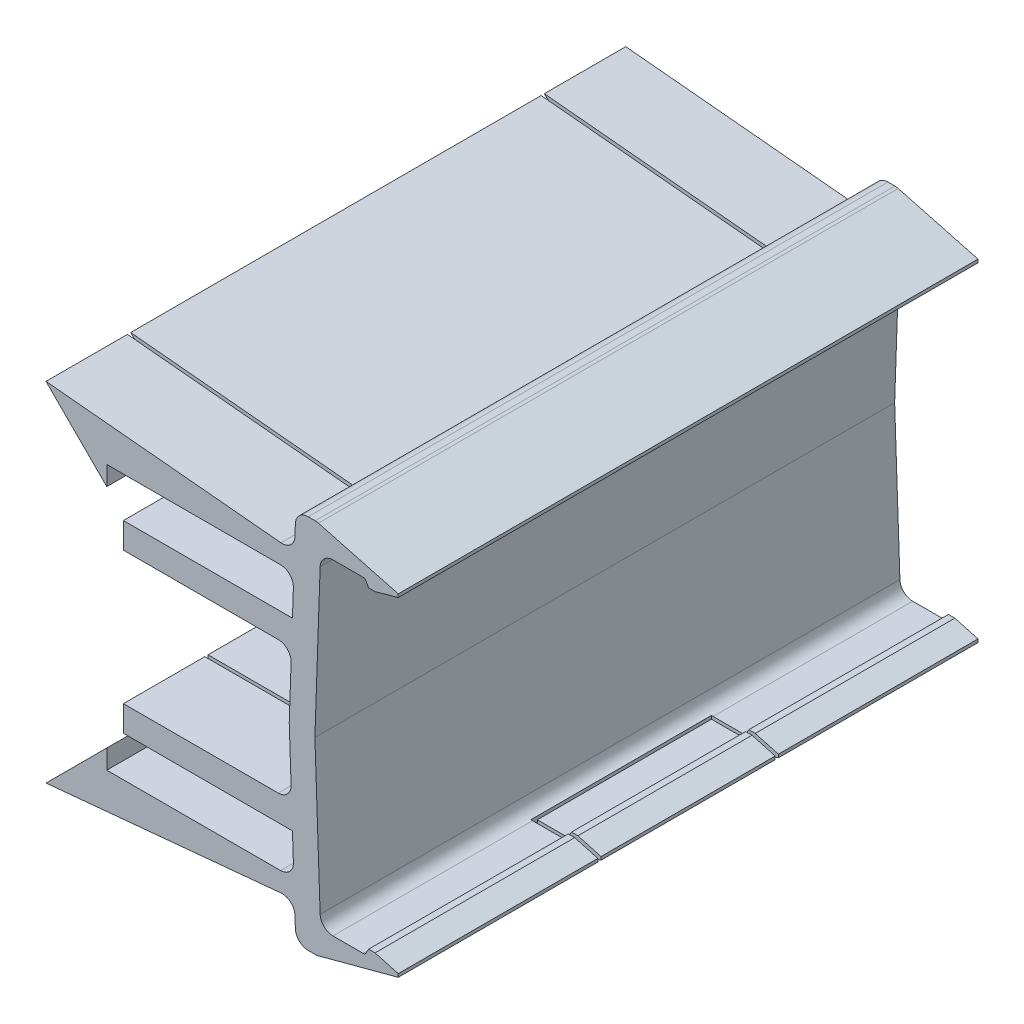
SolidWorks part; units mm, degrees
ref_plane "Front Plane" through (0, 0, 0) normal (0, 0, 1) x (1, 0, 0)
ref_plane "Top Plane" through (0, 0, 0) normal (0, 1, 0) x (1, 0, 0)
ref_plane "Right Plane" through (0, 0, 0) normal (1, 0, 0) x (0, 0, -1)
sketch "Sketch1" plane through (0, 0, 0) normal (0, 0, 1) x (1, 0, 0)
  line L50 (-6.5001, 0) -> (-6.0903, 11.7349) construction
  line L51 (-3.9751, 12.7) -> (-5.0909, 12.7) construction
  line L52 (-3.9751, 12.7) -> (-2.7386, 12.7) construction
  line L53 (-2.5221, 12.575) -> (-2.3056, 12.2) construction
  line L54 (-2.3056, 12.2) -> (-1.8056, 12.2) construction
  line L55 (-1.8056, 12.2) -> (0, 12.7) construction
  line L56 (0, 12.7) -> (0, 12.95) construction
  line L57 (0, 12.95) -> (-6.35, 14.6455) construction
  line L58 (-6.35, 14.6455) -> (-7.9899, 14.6455) construction
  line L59 (-8.5013, 0) -> (-7.9899, 14.6455) construction
  line L60 (-8.5013, 0) -> (-7.9899, -14.6455) construction
  line L61 (-6.35, -14.6455) -> (-7.9899, -14.6455) construction
  line L62 (0, -12.95) -> (-6.35, -14.6455) construction
  line L63 (0, -12.7) -> (0, -12.95) construction
  line L64 (-1.8056, -12.2) -> (0, -12.7) construction
  line L65 (-2.3056, -12.2) -> (-1.8056, -12.2) construction
  line L66 (-2.5221, -12.575) -> (-2.3056, -12.2) construction
  line L67 (-3.9751, -12.7) -> (-2.7386, -12.7) construction
  line L68 (-3.9751, -12.7) -> (-5.0909, -12.7) construction
  line L69 (-6.5001, 0) -> (-6.0903, -11.7349) construction
  line L70 (-6.5001, 0) -> (-6.0903, 11.7349)
  line L71 (-3.9751, 12.7) -> (-5.0909, 12.7)
  line L72 (-3.9751, 12.7) -> (-2.7386, 12.7)
  line L73 (-2.5221, 12.575) -> (-2.3056, 12.2)
  line L74 (-2.3056, 12.2) -> (-1.8056, 12.2)
  line L75 (-1.8056, 12.2) -> (0, 12.7)
  line L76 (0, 12.7) -> (0, 12.95)
  line L77 (0, 12.95) -> (-6.35, 14.6455)
  line L78 (-6.35, 14.6455) -> (-7.9899, 14.6455)
  line L79 (-8.5013, 0) -> (-7.9899, 14.6455)
  line L80 (-8.5013, 0) -> (-7.9899, -14.6455)
  line L81 (-6.35, -14.6455) -> (-7.9899, -14.6455)
  line L82 (0, -12.95) -> (-6.35, -14.6455)
  line L83 (0, -12.7) -> (0, -12.95)
  line L84 (-1.8056, -12.2) -> (0, -12.7)
  line L85 (-2.3056, -12.2) -> (-1.8056, -12.2)
  line L86 (-2.5221, -12.575) -> (-2.3056, -12.2)
  line L87 (-3.9751, -12.7) -> (-2.7386, -12.7)
  line L88 (-3.9751, -12.7) -> (-5.0909, -12.7)
  line L89 (-6.5001, 0) -> (-6.0903, -11.7349)
  arc A10 (-5.0909, 12.7) -> (-6.0903, 11.7349) centre (-5.0909, 11.7) ccw construction
  arc A11 (-2.5221, 12.575) -> (-2.7386, 12.7) centre (-2.7386, 12.45) ccw construction
  arc A12 (-2.7386, -12.7) -> (-2.5221, -12.575) centre (-2.7386, -12.45) ccw construction
  arc A13 (-6.0903, -11.7349) -> (-5.0909, -12.7) centre (-5.0909, -11.7) ccw construction
  arc A14 (-5.0909, 12.7) -> (-6.0903, 11.7349) centre (-5.0909, 11.7) ccw
  arc A15 (-2.5221, 12.575) -> (-2.7386, 12.7) centre (-2.7386, 12.45) ccw
  arc A16 (-2.7386, -12.7) -> (-2.5221, -12.575) centre (-2.7386, -12.45) ccw
  arc A17 (-6.0903, -11.7349) -> (-5.0909, -12.7) centre (-5.0909, -11.7) ccw
extrude "Boss-Extrude1" add sketch "Sketch1" along normal mid plane 6.35
sketch "Sketch3" plane through (0, 0, 0) normal (0, 0, 1) x (1, 0, 0)
  line L1 (-21.435, 5.1835) -> (-8.2505, 5.1835)
  line L2 (-21.435, 5.1835) -> (-21.435, 7.1835)
  line L3 (-21.435, 7.1835) -> (-8.2505, 7.1835)
  line L4 (-8.2505, 5.1835) -> (-8.2505, 7.1835)
  line L5 (-21.435, -10.3251) -> (-21.435, 10.3251) construction
  line L6 (-13.335, 7.6835) -> (-15.875, 7.6835) construction
  line L7 (-7.9899, 14.6455) -> (-8.5013, 0) construction
  dimension "D1" = 2
  dimension "D2" = 0.5
sketch "Sketch2" plane through (0, 0, 0) normal (0, 0, 1) x (1, 0, 0)
  line L0 (-22.7304, 10.3251) -> (-22.7304, 8.8251)
  line L1 (-22.7304, 8.8251) -> (-27.4693, 13.564)
  line L2 (-27.4693, 13.564) -> (-8.0919, 11.7251)
  line L3 (-8.0919, 11.7251) -> (-8.0919, 10.3251)
  line L4 (-8.0919, 10.3251) -> (-22.7304, 10.3251)
  line L5 (-22.7304, 10.3251) -> (-22.7304, 11.3751) construction
  line L6 (-15.875, 10.3251) -> (-17.018, 10.3251) construction
  line L9 (-7.9899, 14.6455) -> (-8.5013, 0) construction
  line L10 (-22.578, -10.3251) -> (-22.578, 10.3251) construction
  dimension "D1" = 1.05
  dimension "D2" = 1.4
  dimension "D4" = 1.5
  dimension "D5" = 45
  dimension "D3" = 0.1524
extrude "Boss-Extrude2" add sketch "Sketch2" along normal up to surface and the other way up to surface
extrude "Boss-Extrude3" add sketch "Sketch3" along normal up to surface and the other way up to surface
fillet "Fillet1" radius 1 5 edges at (-8.3203, 5.1835, 0) (-8.1408, 10.3251, 0) (-8.0919, 11.7251, 0) (-6.35, 14.6455, 0) (-7.9899, 14.6455, 0)
sketch "Sketch9" plane through (0, 0, 0) normal (0, 0, 1) x (1, 0, 0)
  line L7 (-7.9899, -14.6455) -> (-6.35, -14.6455) construction
  line L8 (0, 0) -> (-14.6455, 0)
  line L9 (0, 0) -> (0, -14.6455)
  line L10 (0, -14.6455) -> (-14.6455, -14.6455)
  line L11 (-14.6455, 0) -> (-14.6455, -14.6455)
extrude "Cut-Extrude4" cut sketch "Sketch9" against normal through all both and the other way through all
mirror "Mirror2" about plane through (0, 0, 0) normal (0, 1, 0) of bodies 110 103
ref_plane "Plane1" through (0, 0, 0) normal (0, 0, 1) x (1, 0, 0)
ref_plane "Plane2" through (0, 0, 0) normal (0, 1, 0) x (1, 0, 0)
ref_plane "Plane3" through (0, 0, 0) normal (0, 0, 1) x (1, 0, 0)
ref_plane "Plane4" through (0, 0, 19.431) normal (0, 0, 1) x (1, 0, 0)
ref_plane "Plane5" through (0, 0, 42.037) normal (0, 0, 1) x (1, 0, 0)
sketch "Sketch10" plane through (0, 0, 42.037) normal (0, 0, 1) x (1, 0, 0)
  line L36 (-8.3564, 4.1486) -> (-8.5013, 0)
  line L37 (-8.5013, 0) -> (-8.3564, -4.1486)
  line L38 (-9.3558, -5.1835) -> (-21.435, -5.1835)
  line L39 (-21.435, -5.1835) -> (-21.435, -7.1835)
  line L40 (-21.435, -7.1835) -> (-8.2505, -7.1835)
  line L41 (-8.2505, -7.1835) -> (-8.1769, -9.2902)
  line L42 (-9.1763, -10.3251) -> (-22.7304, -10.3251)
  line L43 (-22.7304, -10.3251) -> (-22.7304, -8.8251)
  line L44 (-22.7304, -8.8251) -> (-27.4693, -13.564)
  line L45 (-27.4693, -13.564) -> (-9.1487, -11.8254)
  line L46 (-8.0548, -12.786) -> (-8.0236, -13.6804)
  line L47 (-7.0242, -14.6455) -> (-6.4812, -14.6455)
  line L48 (-6.2232, -14.6117) -> (0, -12.95)
  line L49 (0, -12.95) -> (0, -12.7)
  line L50 (0, -12.7) -> (-1.8056, -12.2)
  line L51 (-1.8056, -12.2) -> (-2.3056, -12.2)
  line L52 (-2.3056, -12.2) -> (-2.5221, -12.575)
  line L53 (-2.7386, -12.7) -> (-5.0909, -12.7)
  line L54 (-6.0903, -11.7349) -> (-6.5001, 0)
  line L55 (-6.5001, 0) -> (-6.0903, 11.7349)
  line L56 (-5.0909, 12.7) -> (-2.7386, 12.7)
  line L57 (-2.5221, 12.575) -> (-2.3056, 12.2)
  line L58 (-2.3056, 12.2) -> (-1.8056, 12.2)
  line L59 (-1.8056, 12.2) -> (0, 12.7)
  line L60 (0, 12.7) -> (0, 12.95)
  line L61 (0, 12.95) -> (-6.2232, 14.6117)
  line L62 (-6.4812, 14.6455) -> (-7.0242, 14.6455)
  line L63 (-8.0236, 13.6804) -> (-8.0548, 12.786)
  line L64 (-9.1487, 11.8254) -> (-27.4693, 13.564)
  line L65 (-27.4693, 13.564) -> (-22.7304, 8.8251)
  line L66 (-22.7304, 8.8251) -> (-22.7304, 10.3251)
  line L67 (-22.7304, 10.3251) -> (-9.1763, 10.3251)
  line L68 (-8.1769, 9.2902) -> (-8.2505, 7.1835)
  line L69 (-8.2505, 7.1835) -> (-21.435, 7.1835)
  line L70 (-21.435, 7.1835) -> (-21.435, 5.1835)
  line L71 (-21.435, 5.1835) -> (-9.3558, 5.1835)
  line L72 (-8.3564, 4.1486) -> (-8.5013, 0)
  line L73 (-8.5013, 0) -> (-8.3564, -4.1486)
  line L74 (-9.3558, -5.1835) -> (-21.435, -5.1835)
  line L75 (-21.435, -5.1835) -> (-21.435, -7.1835)
  line L76 (-21.435, -7.1835) -> (-8.2505, -7.1835)
  line L77 (-8.2505, -7.1835) -> (-8.1769, -9.2902)
  line L78 (-9.1763, -10.3251) -> (-22.7304, -10.3251)
  line L79 (-22.7304, -10.3251) -> (-22.7304, -8.8251)
  line L80 (-22.7304, -8.8251) -> (-27.4693, -13.564)
  line L81 (-27.4693, -13.564) -> (-9.1487, -11.8254)
  line L82 (-8.0548, -12.786) -> (-8.0236, -13.6804)
  line L83 (-7.0242, -14.6455) -> (-6.4812, -14.6455)
  line L84 (-6.2232, -14.6117) -> (0, -12.95)
  line L85 (0, -12.95) -> (0, -12.7)
  line L86 (0, -12.7) -> (-1.8056, -12.2)
  line L87 (-1.8056, -12.2) -> (-2.3056, -12.2)
  line L88 (-2.3056, -12.2) -> (-2.5221, -12.575)
  line L89 (-2.7386, -12.7) -> (-5.0909, -12.7)
  line L90 (-6.0903, -11.7349) -> (-6.5001, 0)
  line L91 (-6.5001, 0) -> (-6.0903, 11.7349)
  line L92 (-5.0909, 12.7) -> (-2.7386, 12.7)
  line L93 (-2.5221, 12.575) -> (-2.3056, 12.2)
  line L94 (-2.3056, 12.2) -> (-1.8056, 12.2)
  line L95 (-1.8056, 12.2) -> (0, 12.7)
  line L96 (0, 12.7) -> (0, 12.95)
  line L97 (0, 12.95) -> (-6.2232, 14.6117)
  line L98 (-6.4812, 14.6455) -> (-7.0242, 14.6455)
  line L99 (-8.0236, 13.6804) -> (-8.0548, 12.786)
  line L100 (-9.1487, 11.8254) -> (-27.4693, 13.564)
  line L101 (-27.4693, 13.564) -> (-22.7304, 8.8251)
  line L102 (-22.7304, 8.8251) -> (-22.7304, 10.3251)
  line L103 (-22.7304, 10.3251) -> (-9.1763, 10.3251)
  line L104 (-8.1769, 9.2902) -> (-8.2505, 7.1835)
  line L105 (-8.2505, 7.1835) -> (-21.435, 7.1835)
  line L106 (-21.435, 7.1835) -> (-21.435, 5.1835)
  line L107 (-21.435, 5.1835) -> (-9.3558, 5.1835)
  arc A14 (-9.3558, -5.1835) -> (-8.3564, -4.1486) centre (-9.3558, -4.1835) ccw
  arc A15 (-9.1763, -10.3251) -> (-8.1769, -9.2902) centre (-9.1763, -9.3251) ccw
  arc A16 (-8.0548, -12.786) -> (-9.1487, -11.8254) centre (-9.0542, -12.8209) ccw
  arc A17 (-8.0236, -13.6804) -> (-7.0242, -14.6455) centre (-7.0242, -13.6455) ccw
  arc A18 (-6.4812, -14.6455) -> (-6.2232, -14.6117) centre (-6.4812, -13.6455) ccw
  arc A19 (-2.7386, -12.7) -> (-2.5221, -12.575) centre (-2.7386, -12.45) ccw
  arc A20 (-6.0903, -11.7349) -> (-5.0909, -12.7) centre (-5.0909, -11.7) ccw
  arc A21 (-5.0909, 12.7) -> (-6.0903, 11.7349) centre (-5.0909, 11.7) ccw
  arc A22 (-2.5221, 12.575) -> (-2.7386, 12.7) centre (-2.7386, 12.45) ccw
  arc A23 (-6.2232, 14.6117) -> (-6.4812, 14.6455) centre (-6.4812, 13.6455) ccw
  arc A24 (-7.0242, 14.6455) -> (-8.0236, 13.6804) centre (-7.0242, 13.6455) ccw
  arc A25 (-9.1487, 11.8254) -> (-8.0548, 12.786) centre (-9.0542, 12.8209) ccw
  arc A26 (-8.1769, 9.2902) -> (-9.1763, 10.3251) centre (-9.1763, 9.3251) ccw
  arc A27 (-8.3564, 4.1486) -> (-9.3558, 5.1835) centre (-9.3558, 4.1835) ccw
  arc A28 (-9.3558, -5.1835) -> (-8.3564, -4.1486) centre (-9.3558, -4.1835) ccw
  arc A29 (-9.1763, -10.3251) -> (-8.1769, -9.2902) centre (-9.1763, -9.3251) ccw
  arc A30 (-8.0548, -12.786) -> (-9.1487, -11.8254) centre (-9.0542, -12.8209) ccw
  arc A31 (-8.0236, -13.6804) -> (-7.0242, -14.6455) centre (-7.0242, -13.6455) ccw
  arc A32 (-6.4812, -14.6455) -> (-6.2232, -14.6117) centre (-6.4812, -13.6455) ccw
  arc A33 (-2.7386, -12.7) -> (-2.5221, -12.575) centre (-2.7386, -12.45) ccw
  arc A34 (-6.0903, -11.7349) -> (-5.0909, -12.7) centre (-5.0909, -11.7) ccw
  arc A35 (-5.0909, 12.7) -> (-6.0903, 11.7349) centre (-5.0909, 11.7) ccw
  arc A36 (-2.5221, 12.575) -> (-2.7386, 12.7) centre (-2.7386, 12.45) ccw
  arc A37 (-6.2232, 14.6117) -> (-6.4812, 14.6455) centre (-6.4812, 13.6455) ccw
  arc A38 (-7.0242, 14.6455) -> (-8.0236, 13.6804) centre (-7.0242, 13.6455) ccw
  arc A39 (-9.1487, 11.8254) -> (-8.0548, 12.786) centre (-9.0542, 12.8209) ccw
  arc A40 (-8.1769, 9.2902) -> (-9.1763, 10.3251) centre (-9.1763, 9.3251) ccw
  arc A41 (-8.3564, 4.1486) -> (-9.3558, 5.1835) centre (-9.3558, 4.1835) ccw
  dimension "D1" = 0
extrude "Boss-Extrude4" add sketch "Sketch10" against normal blind 6.35 separate body
sketch "Sketch11" plane through (0, 0, 3.175) normal (0, 0, 1) x (1, 0, 0)
  line L1 (-6.0903, 11.7349) -> (-6.5001, 0)
  line L36 (-8.3564, 4.1486) -> (-8.5013, 0)
  line L37 (-8.5013, 0) -> (-8.3564, -4.1486)
  line L38 (-9.3558, -5.1835) -> (-21.435, -5.1835)
  line L39 (-21.435, -5.1835) -> (-21.435, -7.1835)
  line L40 (-21.435, -7.1835) -> (-8.2505, -7.1835)
  line L41 (-8.2505, -7.1835) -> (-8.1769, -9.2902)
  line L42 (-9.1763, -10.3251) -> (-22.7304, -10.3251)
  line L43 (-22.7304, -10.3251) -> (-22.7304, -8.8251)
  line L44 (-22.7304, -8.8251) -> (-27.4693, -13.564)
  line L45 (-27.4693, -13.564) -> (-9.1487, -11.8254)
  line L46 (-8.0548, -12.786) -> (-8.0236, -13.6804)
  line L47 (-7.0242, -14.6455) -> (-6.4812, -14.6455)
  line L48 (-6.2232, -14.6117) -> (0, -12.95)
  line L49 (0, -12.95) -> (0, -12.7)
  line L50 (0, -12.7) -> (-1.8056, -12.2)
  line L51 (-1.8056, -12.2) -> (-2.3056, -12.2)
  line L52 (-2.3056, -12.2) -> (-2.5221, -12.575)
  line L53 (-2.7386, -12.7) -> (-5.0909, -12.7)
  line L54 (-6.0903, -11.7349) -> (-6.5001, 0)
  line L55 (-6.5001, 0) -> (-6.0903, 11.7349)
  line L56 (-5.0909, 12.7) -> (-2.7386, 12.7)
  line L57 (-2.5221, 12.575) -> (-2.3056, 12.2)
  line L58 (-2.3056, 12.2) -> (-1.8056, 12.2)
  line L59 (-1.8056, 12.2) -> (0, 12.7)
  line L60 (0, 12.7) -> (0, 12.95)
  line L61 (0, 12.95) -> (-6.2232, 14.6117)
  line L62 (-6.4812, 14.6455) -> (-7.0242, 14.6455)
  line L63 (-8.0236, 13.6804) -> (-8.0548, 12.786)
  line L64 (-9.1487, 11.8254) -> (-27.4693, 13.564)
  line L65 (-27.4693, 13.564) -> (-22.7304, 8.8251)
  line L66 (-22.7304, 8.8251) -> (-22.7304, 10.3251)
  line L67 (-22.7304, 10.3251) -> (-9.1763, 10.3251)
  line L68 (-8.1769, 9.2902) -> (-8.2505, 7.1835)
  line L69 (-8.2505, 7.1835) -> (-21.435, 7.1835)
  line L70 (-21.435, 7.1835) -> (-21.435, 5.1835)
  line L71 (-21.435, 5.1835) -> (-9.3558, 5.1835)
  line L72 (-8.0236, 13.6804) -> (-8.5013, 0)
  line L73 (-8.5013, 0) -> (-8.0236, -13.6804)
  line L83 (-7.0242, -14.6455) -> (-6.4812, -14.6455)
  line L84 (-6.2232, -14.6117) -> (0, -12.95)
  line L85 (0, -12.95) -> (0, -12.7)
  line L86 (0, -12.7) -> (-1.8056, -12.2)
  line L87 (-1.8056, -12.2) -> (-2.3056, -12.2)
  line L88 (-2.3056, -12.2) -> (-2.5221, -12.575)
  line L89 (-2.7386, -12.7) -> (-5.0909, -12.7)
  line L90 (-6.0903, -11.7349) -> (-6.5001, 0)
  line L92 (-5.0909, 12.7) -> (-2.7386, 12.7)
  line L93 (-2.5221, 12.575) -> (-2.3056, 12.2)
  line L94 (-2.3056, 12.2) -> (-1.8056, 12.2)
  line L95 (-1.8056, 12.2) -> (0, 12.7)
  line L96 (0, 12.7) -> (0, 12.95)
  line L97 (0, 12.95) -> (-6.2232, 14.6117)
  line L98 (-6.4812, 14.6455) -> (-7.0242, 14.6455)
  arc A14 (-9.3558, -5.1835) -> (-8.3564, -4.1486) centre (-9.3558, -4.1835) ccw
  arc A15 (-9.1763, -10.3251) -> (-8.1769, -9.2902) centre (-9.1763, -9.3251) ccw
  arc A16 (-8.0548, -12.786) -> (-9.1487, -11.8254) centre (-9.0542, -12.8209) ccw
  arc A17 (-8.0236, -13.6804) -> (-7.0242, -14.6455) centre (-7.0242, -13.6455) ccw
  arc A18 (-6.4812, -14.6455) -> (-6.2232, -14.6117) centre (-6.4812, -13.6455) ccw
  arc A19 (-2.7386, -12.7) -> (-2.5221, -12.575) centre (-2.7386, -12.45) ccw
  arc A20 (-6.0903, -11.7349) -> (-5.0909, -12.7) centre (-5.0909, -11.7) ccw
  arc A21 (-5.0909, 12.7) -> (-6.0903, 11.7349) centre (-5.0909, 11.7) ccw
  arc A22 (-2.5221, 12.575) -> (-2.7386, 12.7) centre (-2.7386, 12.45) ccw
  arc A23 (-6.2232, 14.6117) -> (-6.4812, 14.6455) centre (-6.4812, 13.6455) ccw
  arc A24 (-7.0242, 14.6455) -> (-8.0236, 13.6804) centre (-7.0242, 13.6455) ccw
  arc A25 (-9.1487, 11.8254) -> (-8.0548, 12.786) centre (-9.0542, 12.8209) ccw
  arc A26 (-8.1769, 9.2902) -> (-9.1763, 10.3251) centre (-9.1763, 9.3251) ccw
  arc A27 (-8.3564, 4.1486) -> (-9.3558, 5.1835) centre (-9.3558, 4.1835) ccw
  arc A31 (-8.0236, -13.6804) -> (-7.0242, -14.6455) centre (-7.0242, -13.6455) ccw
  arc A32 (-6.4812, -14.6455) -> (-6.2232, -14.6117) centre (-6.4812, -13.6455) ccw
  arc A33 (-2.7386, -12.7) -> (-2.5221, -12.575) centre (-2.7386, -12.45) ccw
  arc A34 (-6.0903, -11.7349) -> (-5.0909, -12.7) centre (-5.0909, -11.7) ccw
  arc A35 (-5.0909, 12.7) -> (-6.0903, 11.7349) centre (-5.0909, 11.7) ccw
  arc A36 (-2.5221, 12.575) -> (-2.7386, 12.7) centre (-2.7386, 12.45) ccw
  arc A37 (-6.2232, 14.6117) -> (-6.4812, 14.6455) centre (-6.4812, 13.6455) ccw
  arc A38 (-7.0242, 14.6455) -> (-8.0236, 13.6804) centre (-7.0242, 13.6455) ccw
  dimension "D1" = 0
extrude "Boss-Extrude5" add sketch "Sketch11" along normal up to surface (32.512 mm away) contours L72 L73 A31 L83 A32 L84 L85 L86 L87 L88 A33 L89 A34 L90 L1 A35 L92 A36 L93 L94 L95 L96 L97 A37 L98 A38 up to face at (-9.274, 0, 35.687)
sketch "Sketch12" plane through (0, -14.6455, 0) normal (0, -1, 0) x (1, 0, 0)
  line L6 (2.3779, 12.391) -> (-5.218, 12.391)
  line L7 (-5.218, 12.391) -> (-5.218, 26.471)
  line L8 (-5.218, 26.471) -> (2.3779, 26.471)
  line L12 (2.3779, 12.391) -> (2.3779, 26.471)
extrude "Cut-Extrude5" cut sketch "Sketch12" against normal blind 6.35
ref_plane "Plane6" through (0, 0, 3.425) normal (0, 0, 1) x (1, 0, 0)
sketch "Sketch13" plane through (0, 0, 3.425) normal (0, 0, 1) x (1, 0, 0)
  line L1 (-9.1763, -10.3251) -> (-22.7304, -10.3251) construction
  line L2 (-22.7304, -10.3251) -> (-22.7304, -8.8251) construction
  line L3 (-22.7304, -8.8251) -> (-27.4693, -13.564) construction
  line L4 (-27.4693, -13.564) -> (-9.1487, -11.8254) construction
  line L5 (-21.435, -7.1835) -> (-8.2505, -7.1835) construction
  line L7 (-9.3558, -5.1835) -> (-21.435, -5.1835) construction
  line L8 (-21.435, -5.1835) -> (-21.435, -7.1835) construction
  line L10 (-8.2505, 7.1835) -> (-21.435, 7.1835) construction
  line L11 (-21.435, 7.1835) -> (-21.435, 5.1835) construction
  line L12 (-21.435, 5.1835) -> (-9.3558, 5.1835) construction
  line L14 (-9.1487, 11.8254) -> (-27.4693, 13.564) construction
  line L15 (-27.4693, 13.564) -> (-22.7304, 8.8251) construction
  line L16 (-22.7304, 8.8251) -> (-22.7304, 10.3251) construction
  line L17 (-22.7304, 10.3251) -> (-9.1763, 10.3251) construction
  line L18 (-8.3277, -12.1337) -> (-8.4037, -9.96)
  line L19 (-9.1763, -10.3251) -> (-22.7304, -10.3251)
  line L20 (-22.7304, -10.3251) -> (-22.7304, -8.8251)
  line L21 (-22.7304, -8.8251) -> (-27.4693, -13.564)
  line L22 (-27.4693, -13.564) -> (-9.1487, -11.8254)
  line L23 (-21.435, -7.1835) -> (-8.5006, -7.1835)
  line L24 (-8.5006, -7.1835) -> (-8.5832, -4.8184)
  line L25 (-9.3558, -5.1835) -> (-21.435, -5.1835)
  line L26 (-21.435, -5.1835) -> (-21.435, -7.1835)
  line L27 (-8.5832, 4.8184) -> (-8.5006, 7.1835)
  line L28 (-8.5006, 7.1835) -> (-21.435, 7.1835)
  line L29 (-21.435, 7.1835) -> (-21.435, 5.1835)
  line L30 (-21.435, 5.1835) -> (-9.3558, 5.1835)
  line L31 (-8.4037, 9.96) -> (-8.3277, 12.1337)
  line L32 (-9.1487, 11.8254) -> (-27.4693, 13.564)
  line L33 (-27.4693, 13.564) -> (-22.7304, 8.8251)
  line L34 (-22.7304, 8.8251) -> (-22.7304, 10.3251)
  line L35 (-22.7304, 10.3251) -> (-9.1763, 10.3251)
  line L36 (-8.0548, 12.786) -> (-8.1769, 9.2902) construction
  line L37 (-8.2505, 7.1835) -> (-8.3564, 4.1486) construction
  line L38 (-8.3564, -4.1486) -> (-8.2505, -7.1835) construction
  line L39 (-8.1769, -9.2902) -> (-8.0548, -12.786) construction
  arc A0 (-8.0548, -12.786) -> (-9.1487, -11.8254) centre (-9.0542, -12.8209) ccw construction
  arc A1 (-9.1763, -10.3251) -> (-8.1769, -9.2902) centre (-9.1763, -9.3251) ccw construction
  arc A2 (-9.3558, -5.1835) -> (-8.3564, -4.1486) centre (-9.3558, -4.1835) ccw construction
  arc A3 (-8.3564, 4.1486) -> (-9.3558, 5.1835) centre (-9.3558, 4.1835) ccw construction
  arc A4 (-8.1769, 9.2902) -> (-9.1763, 10.3251) centre (-9.1763, 9.3251) ccw construction
  arc A5 (-9.1487, 11.8254) -> (-8.0548, 12.786) centre (-9.0542, 12.8209) ccw construction
  arc A6 (-8.3277, -12.1337) -> (-9.1487, -11.8254) centre (-9.0542, -12.8209) ccw
  arc A7 (-9.1763, -10.3251) -> (-8.4037, -9.96) centre (-9.1763, -9.3251) ccw
  arc A8 (-9.3558, -5.1835) -> (-8.5832, -4.8184) centre (-9.3558, -4.1835) ccw
  arc A9 (-8.5832, 4.8184) -> (-9.3558, 5.1835) centre (-9.3558, 4.1835) ccw
  arc A10 (-8.4037, 9.96) -> (-9.1763, 10.3251) centre (-9.1763, 9.3251) ccw
  arc A11 (-9.1487, 11.8254) -> (-8.3277, 12.1337) centre (-9.0542, 12.8209) ccw
  dimension "D1" = 0.25
  dimension "D2" = 0.25
  dimension "D3" = 0.25
  dimension "D4" = 0.25
extrude "Boss-Extrude6" add sketch "Sketch13" along normal offset from surface (32.012 mm away) 0.25 separate body up to face at (-13.7226, -5.8189, 35.687)
ref_plane "Plane7" through (0, 0, 12.641) normal (0, 0, 1) x (1, 0, 0)
sketch "Sketch14" plane through (0, 0, 12.641) normal (0, 0, 1) x (1, 0, 0)
  line L0 (-5.218, -12.6919) -> (-5.218, -14.3433) construction
  line L7 (-5.218, -12.6919) -> (-5.218, -14.3433)
  line L8 (-5.218, -14.3433) -> (0, -12.95)
  line L9 (0, -12.95) -> (0, -12.7)
  line L10 (0, -12.7) -> (-1.8056, -12.2)
  line L11 (-1.8056, -12.2) -> (-2.3056, -12.2)
  line L12 (-2.3056, -12.2) -> (-2.5221, -12.575)
  line L13 (-2.7386, -12.7) -> (-5.0909, -12.7)
  line L14 (-4.968, -12.7) -> (-4.968, -14.2765)
  line L15 (-4.968, -14.2765) -> (0, -12.95)
  line L16 (0, -12.95) -> (0, -12.7)
  line L17 (0, -12.7) -> (-1.8056, -12.2)
  line L18 (-1.8056, -12.2) -> (-2.3056, -12.2)
  line L19 (-2.3056, -12.2) -> (-2.5221, -12.575)
  line L20 (-2.7386, -12.7) -> (-4.968, -12.7)
  arc A2 (-2.7386, -12.7) -> (-2.5221, -12.575) centre (-2.7386, -12.45) ccw
  arc A3 (-5.218, -12.6919) -> (-5.0909, -12.7) centre (-5.0909, -11.7) ccw
  arc A4 (-2.7386, -12.7) -> (-2.5221, -12.575) centre (-2.7386, -12.45) ccw
  dimension "D2" = 0.25
  dimension "D1" = 0
extrude "Boss-Extrude7" add sketch "Sketch14" along normal offset from surface (13.58 mm away) 0.25 separate body up to face at (-2.7647, -12.7879, 26.471)
equation "\"t\"= .35mm"
equation "\"D1@Sketch2\"=\"t\"*3"
equation "\"D2@Sketch2\"=\"t\"*4"
